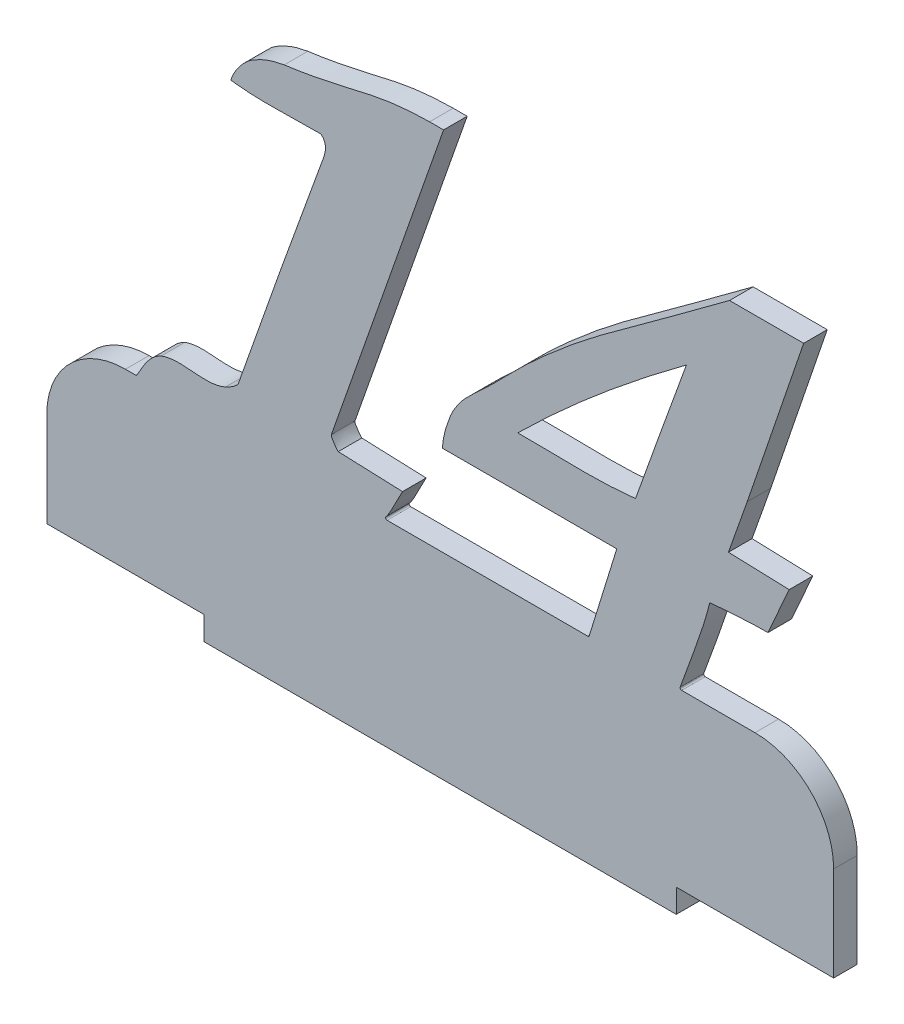
SolidWorks part; units mm, degrees
ref_plane "Front Plane" through (0, 0, 0) normal (0, 0, 1) x (1, 0, 0)
ref_plane "Top Plane" through (0, 0, 0) normal (0, 1, 0) x (1, 0, 0)
ref_plane "Right Plane" through (0, 0, 0) normal (1, 0, 0) x (0, 0, -1)
sketch "Sketch1" plane through (0, 0, 0) normal (0, 0, 1) x (1, 0, 0)
  line L0 (0, 20) -> (100, 20) construction
  line L1 (42.7496, 22) -> (68.9003, 22)
  line L2 (0, 22) -> (0, 0)
  line L3 (0, 0) -> (20, 0)
  line L4 (100, 22) -> (100, 0)
  line L5 (0, 22) -> (11.4068, 22)
  line L6 (90.1102, 22) -> (100, 22)
  line L7 (50.4293, 68.5554) -> (36.1799, 27.9182)
  line L8 (37.0399, 26.4522) -> (45.2104, 26.1395)
  line L9 (94.3503, 39.9198) -> (91.6529, 33.8408)
  line L10 (80.4029, 22) -> (90.1102, 22)
  line L11 (80, 0) -> (100, 0)
  line L12 (68.9003, 22) -> (72.4387, 33.4499)
  line L13 (20, 0) -> (20, -3)
  line L14 (20, -3) -> (80, -3)
  line L15 (80, 0) -> (80, -3)
  line L16 (72.4387, 33.4499) -> (50.2729, 33.4499)
  line L17 (86.7663, 67.9495) -> (96.1877, 67.9495)
  line L18 (96.1877, 67.9495) -> (89.0141, 46.9174)
  line L19 (89.0141, 46.9174) -> (86.6294, 40.1739)
  line L20 (86.6294, 40.1739) -> (94.3503, 39.9198)
  spline S0 degree 3 poles (45.2104, 26.1395) (44.6154, 25.1263) (44.0703, 23.804) (43.2195, 22.4149) (42.89, 22.1114) (42.7496, 22) knots 0 0 0 0 0.504343 0.619768 0.696711 0.696711 0.696711 0.696711
  spline S1 degree 3 poles (11.4068, 22) (11.4819, 22.1283) (11.8039, 22.6903) (12.6065, 24.1299) (13.6011, 25.2995) (14.5419, 25.729) knots 0.174412 0.174412 0.174412 0.174412 0.248912 0.498933 1 1 1 1
  spline S2 degree 3 poles (14.5419, 25.729) (15.8832, 26.2483) (18.634, 25.9735) (21.4033, 25.8178) (22.7123, 26.3936) knots 0 0 0 0 0.501452 1 1 1 1
  spline S3 degree 2 poles (22.7123, 26.3936) (23.5938, 26.7841) (24.2956, 27.4491) knots 0 0 0 1 1 1
  spline S4 degree 3 poles (24.2956, 27.4491) (26.0779, 32.4843) (29.6029, 42.6071) (33.2919, 52.6713) (35.1243, 57.7267) knots 0 0 0 0 0.498323 1 1 1 1
  spline S5 degree 3 poles (35.1243, 57.7267) (35.3075, 58.2242) (35.6027, 59.1908) (35.1501, 60.1022) (34.7921, 60.3068) knots 0 0 0 0 0.581397 1 1 1 1
  spline S6 degree 3 poles (34.7921, 60.3068) (32.8753, 60.3406) (29.0703, 60.1567) (25.2574, 60.2614) (23.3769, 60.5023) knots 0 0 0 0 0.503015 1 1 1 1
  spline S7 degree 3 poles (23.3769, 60.5023) (23.6089, 61.1694) (24.0931, 62.1184) (25.0111, 63.1791) (25.7844, 63.9016) (26.7323, 64.4554) (28.1594, 65.1381) (29.3514, 65.4529) (30.1791, 65.5844) knots 0 0 0 0 0.237267 0.352024 0.469659 0.590381 0.718477 1 1 1 1
  spline S8 degree 3 poles (30.1791, 65.5844) (33.2913, 65.9828) (37.1531, 66.8348) (41.7749, 67.9146) (44.8548, 68.3971) (47.1479, 68.5446) (48.6505, 68.5554) knots 0 0 0 0 0.501478 0.63281 0.759518 1 1 1 1
  spline S9 degree 3 poles (48.6505, 68.5554) (48.859, 68.5554) (49.4519, 68.5554) (50.0449, 68.5554) (50.4293, 68.5554) knots 0 0 0 0 0.351648 1 1 1 1
  spline S10 degree 3 poles (36.1799, 27.9182) (36.1267, 27.7184) (36.4583, 27.2087) (36.736, 26.7259) (37.0399, 26.4522) knots 0 0 0 0 0.324502 1 1 1 1
  spline S11 degree 3 poles (81.2932, 58.1176) (77.3364, 55.1908) (69.9663, 49.3752) (63.0243, 43.0546) (59.8507, 39.9198) knots 0 0 0 0 0.524587 1 1 1 1
  spline S12 degree 3 poles (59.8507, 39.9198) (62.347, 39.9561) (67.3387, 39.7556) (72.337, 39.8989) (74.8233, 40.1739) knots 0 0 0 0 0.499666 1 1 1 1
  spline S13 degree 3 poles (74.8233, 40.1739) (75.9292, 43.1665) (78.0175, 49.1722) (80.1999, 55.1443) (81.2932, 58.1176) knots 0 0 0 0 0.501754 1 1 1 1
  spline S14 degree 3 poles (91.6529, 33.8408) (90.6158, 33.8497) (88.1513, 33.729) (85.6891, 33.5791) (84.2643, 33.4499) knots 0 0 0 0 0.420206 1 1 1 1
  spline S15 degree 3 poles (84.2643, 33.4499) (83.7519, 31.3629) (82.7075, 28.3217) (81.3194, 24.5391) (80.6764, 22.7688) (80.4029, 22) knots 0 0 0 0 0.502209 0.752081 0.943038 0.943038 0.943038 0.943038
  spline S16 degree 2 poles (50.2729, 33.4499) (50.3997, 35.2321) (51.0743, 36.8901) knots 0 0 0 1 1 1
  spline S17 degree 3 poles (51.0743, 36.8901) (51.3253, 37.6943) (51.9184, 38.8236) (52.9654, 40.1974) (55.0403, 42.2264) (56.9061, 43.8422) (58.2674, 45.3342) knots 0 0 0 0 0.224443 0.338858 0.460951 1 1 1 1
  spline S18 degree 3 poles (58.2674, 45.3342) (60.3848, 47.5214) (63.7976, 50.6865) (68.6932, 54.688) (72.6432, 57.6221) (76.5612, 60.4435) (81.2648, 63.8758) (84.6345, 66.3502) (86.7663, 67.9495) knots 0 0 0 0 0.250612 0.382932 0.520503 0.655731 0.780544 1 1 1 1
  dimension "D1" = 100
  dimension "D2" = 3
  dimension "D3" = 20
  dimension "D4" = 20
  dimension "D5" = 20
extrude "Boss-Extrude1" add sketch "Sketch1" along normal blind 3
fillet "Fillet1" radius 10 2 edges at (0, 22, 1.5) (100, 22, 1.5)
fillet "Fillet2" radius 0.2 4 edges at (80.4029, 22, 1.5) (42.7496, 22, 1.5) (68.9003, 22, 1.5) (11.4068, 22, 1.5)
